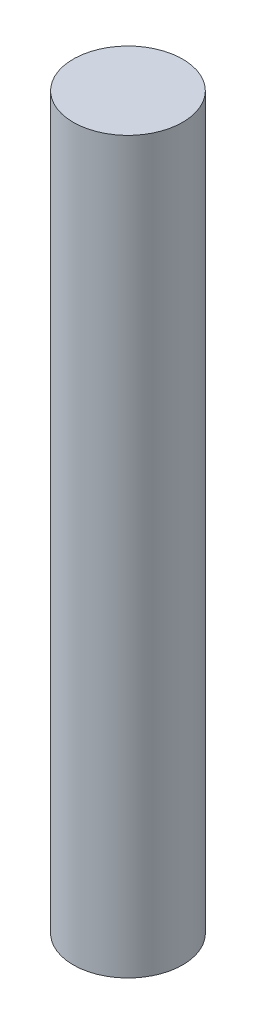
SolidWorks part; units mm, degrees
ref_plane "前视基准面" through (0, 0, 0) normal (0, 0, 1) x (1, 0, 0)
ref_plane "上视基准面" through (0, 0, 0) normal (0, 1, 0) x (1, 0, 0)
ref_plane "右视基准面" through (0, 0, 0) normal (1, 0, 0) x (0, 0, -1)
other "Configuration Table"
sketch "草图1" plane through (0, 0, 0) normal (0, 1, 0) x (1, 0, 0)
  circle A0 centre (0, 0) radius 1.5
  dimension "D1" = 3
extrude "凸台-拉伸1" add sketch "草图1" along normal blind 20
